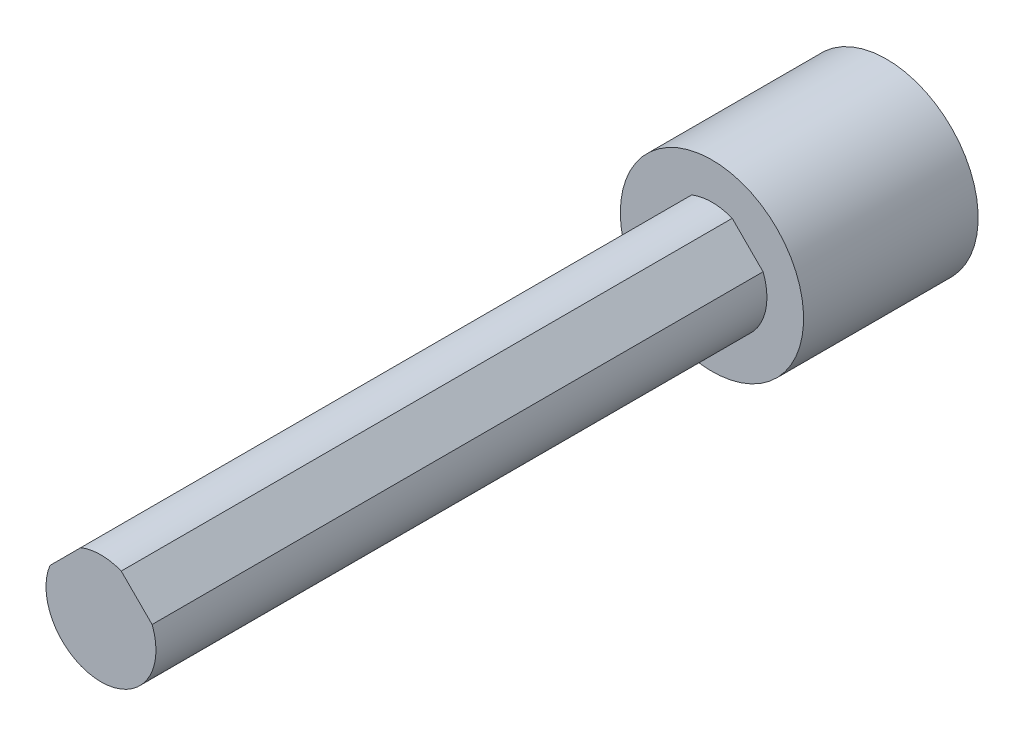
SolidWorks part; units mm, degrees
ref_plane "Front Plane" through (0, 0, 0) normal (0, 0, 1) x (1, 0, 0)
ref_plane "Top Plane" through (0, 0, 0) normal (0, 1, 0) x (1, 0, 0)
ref_plane "Right Plane" through (0, 0, 0) normal (1, 0, 0) x (0, 0, -1)
sketch "Sketch1" plane through (0, 0, 0) normal (0, 0, 1) x (1, 0, 0)
  line L0 (-1.474, 3.7191) -> (-3.7191, 1.474)
  line L1 (0, 0) -> (0, 3.8629) construction
  line L2 (1.474, 3.7191) -> (3.7191, 1.474)
  arc A0 (-3.7191, 1.474) -> (3.7191, 1.474) centre (0, 0) ccw
  arc A1 (1.474, 3.7191) -> (-1.474, 3.7191) centre (0, 0) ccw
  dimension "D1" = 8.001
  dimension "D2" = 90
  dimension "D3" = 3.175
extrude "Boss-Extrude1" add sketch "Sketch1" along normal blind 44.45
sketch "Sketch2" plane through (0, 0, 0) normal (0, 0, -1) x (-1, 0, 0)
  circle A0 centre (0, 0) radius 6.6675
  dimension "D1" = 13.335
extrude "Boss-Extrude2" add sketch "Sketch2" along normal blind 12.7
